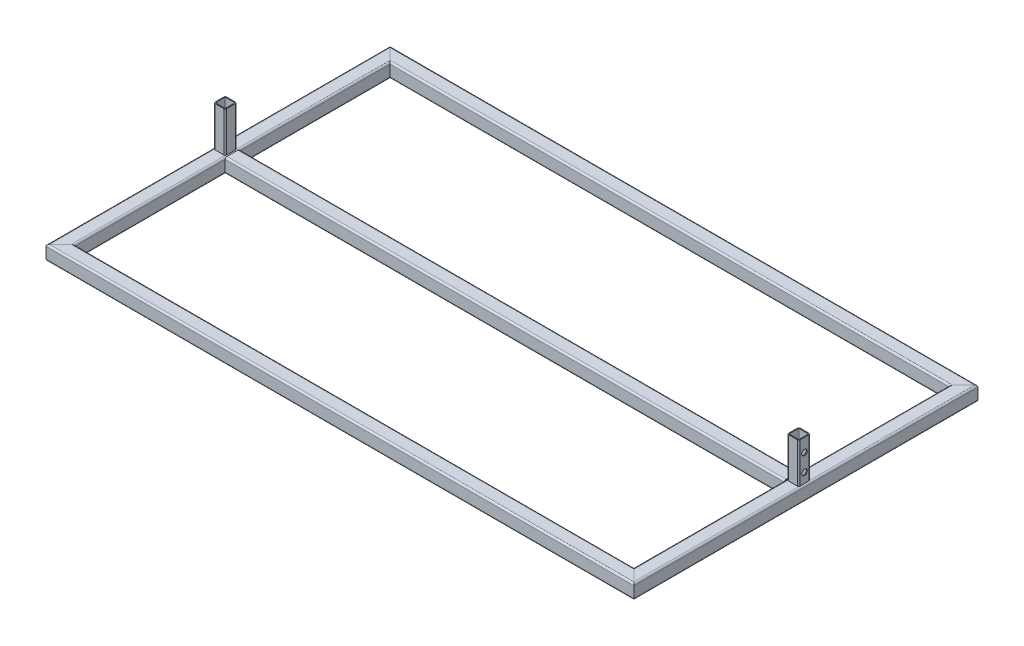
SolidWorks part; units mm, degrees
ref_plane "Спереди" through (0, 0, 0) normal (0, 0, 1) x (1, 0, 0)
ref_plane "Сверху" through (0, 0, 0) normal (0, 1, 0) x (1, 0, 0)
ref_plane "Справа" through (0, 0, 0) normal (1, 0, 0) x (0, 0, -1)
sketch "Эскиз1" plane through (0, 0, 0) normal (0, 1, 0) x (1, 0, 0)
  line L1 (-500, -287.5) -> (500, -287.5)
  line L2 (-500, -287.5) -> (-500, 287.5)
  line L3 (-500, 287.5) -> (500, 287.5)
  line L4 (500, -287.5) -> (500, 287.5)
  line L5 (0, 287.5) -> (0, -287.5) construction
  line L6 (-500, 0) -> (500, 0)
  point P0 (0, 0)
  dimension "D1" = 575
  dimension "D2" = 1000
sketch3d "Трехмерный эскиз1"
  line L0 (-500, 0, 0) -> (-500, 82.5, 0)
  line L1 (500, 0, 0) -> (500, 82.5, 0)
  dimension "D1" = 82.5
other "Square tube - configured 20 X 20 X 2(1)"
ref_plane "Плоскость1" through (-500, 0, -287.5) normal (1, 0, 0) x (0, 0, -1)
sketch "Sketch11" plane through (-500, 0, -287.5) normal (1, 0, 0) x (0, 0, -1)
  line L0 (-9.5, -11) -> (9.5, -11)
  line L1 (-11, -9.5) -> (-11, 9.5)
  line L2 (9.5, 11) -> (-9.5, 11)
  line L3 (11, 9.5) -> (11, -9.5)
  line L4 (-9.5, -12.5) -> (9.5, -12.5)
  line L5 (-12.5, -9.5) -> (-12.5, 9.5)
  line L6 (9.5, 12.5) -> (-9.5, 12.5)
  line L7 (12.5, 9.5) -> (12.5, -9.5)
  arc A0 (12.5, 9.5) -> (9.5, 12.5) centre (9.5, 9.5) ccw
  arc A1 (9.5, -12.5) -> (12.5, -9.5) centre (9.5, -9.5) ccw
  arc A2 (-12.5, -9.5) -> (-9.5, -12.5) centre (-9.5, -9.5) ccw
  arc A3 (-9.5, 12.5) -> (-12.5, 9.5) centre (-9.5, 9.5) ccw
  arc A4 (-9.5, 11) -> (-11, 9.5) centre (-9.5, 9.5) ccw
  arc A5 (11, 9.5) -> (9.5, 11) centre (9.5, 9.5) ccw
  arc A6 (9.5, -11) -> (11, -9.5) centre (9.5, -9.5) ccw
  arc A7 (-11, -9.5) -> (-9.5, -11) centre (-9.5, -9.5) ccw
  point P0 (-12.5, 0)
  point P1 (12.5, 0)
  point P2 (0, 12.5)
  point P3 (0, -12.5)
  point P4 (0, 0)
  point P5 (-12.5, -12.5)
  point P6 (12.5, -12.5)
  point P7 (12.5, 12.5)
  point P8 (-12.5, 12.5)
  point P33 (0, 0)
  dimension "D1" = 3
  dimension "Thickness" = 1.5
  dimension "V_leg" = 25
other "Square tube - configured 20 X 20 X 2(2)"
ref_plane "Плоскость2" through (-500, 0, 0) normal (0, 1, 0) x (1, 0, 0)
sketch "Sketch1" plane through (-500, 0, 0) normal (0, 1, 0) x (1, 0, 0)
  line L0 (-7.5, -8.5) -> (7.5, -8.5)
  line L1 (-8.5, -7.5) -> (-8.5, 7.5)
  line L2 (7.5, 8.5) -> (-7.5, 8.5)
  line L3 (8.5, 7.5) -> (8.5, -7.5)
  line L4 (-7.5, -10) -> (7.5, -10)
  line L5 (-10, -7.5) -> (-10, 7.5)
  line L6 (7.5, 10) -> (-7.5, 10)
  line L7 (10, 7.5) -> (10, -7.5)
  arc A0 (10, 7.5) -> (7.5, 10) centre (7.5, 7.5) ccw
  arc A1 (7.5, -10) -> (10, -7.5) centre (7.5, -7.5) ccw
  arc A2 (-10, -7.5) -> (-7.5, -10) centre (-7.5, -7.5) ccw
  arc A3 (-7.5, 10) -> (-10, 7.5) centre (-7.5, 7.5) ccw
  arc A4 (-7.5, 8.5) -> (-8.5, 7.5) centre (-7.5, 7.5) ccw
  arc A5 (8.5, 7.5) -> (7.5, 8.5) centre (7.5, 7.5) ccw
  arc A6 (7.5, -8.5) -> (8.5, -7.5) centre (7.5, -7.5) ccw
  arc A7 (-8.5, -7.5) -> (-7.5, -8.5) centre (-7.5, -7.5) ccw
  point P0 (-10, 0)
  point P1 (10, 0)
  point P2 (0, 10)
  point P3 (0, -10)
  point P4 (0, 0)
  point P5 (-10, -10)
  point P6 (10, -10)
  point P7 (10, 10)
  point P8 (-10, 10)
  point P33 (0, 0)
  dimension "D1" = 2.5
  dimension "Thickness" = 1.5
  dimension "V_leg" = 20
other "Отсечь/Удлинить1"
sketch "Эскиз3" plane through (0, -12.5, 0) normal (0, -1, 0) x (-1, 0, 0)
  line L1 (500, -287.5) -> (461.8661, -287.5) construction
  line L2 (509.5, -297) -> (490.5, -278) construction
  line L4 (482.1132, -292.5) -> (487.8868, -292.5)
  line L5 (487.8868, -292.5) -> (490.7735, -287.5)
  line L6 (490.7735, -287.5) -> (487.8868, -282.5)
  line L7 (487.8868, -282.5) -> (482.1132, -282.5)
  line L8 (482.1132, -282.5) -> (479.2265, -287.5)
  line L9 (479.2265, -287.5) -> (482.1132, -292.5)
  circle A1 centre (485, -287.5) radius 5 construction
  dimension "D1" = 10
  dimension "D2" = 15
extrude "Вырез-Вытянуть2" cut sketch "Эскиз3" against normal blind 5
mirror "Зеркальное отражение1" about plane through (0, 0, 0) normal (1, 0, 0) of "Вырез-Вытянуть2"
mirror "Зеркальное отражение2" about plane through (0, 0, 0) normal (0, 0, 1) of "Зеркальное отражение1", "Вырез-Вытянуть2"
ref_plane "Плоскость3" through (-500, 0, 0) normal (1, 0, 0) x (0, 0, -1)
sketch "Эскиз4" plane through (-510, 0, 0) normal (1, 0, 0) x (0, 0, -1)
  line L1 (-5.3116, 59.5) -> (-2.6558, 54.9)
  line L2 (-2.6558, 54.9) -> (2.6558, 54.9)
  line L3 (2.6558, 54.9) -> (5.3116, 59.5)
  line L4 (5.3116, 59.5) -> (2.6558, 64.1)
  line L5 (2.6558, 64.1) -> (-2.6558, 64.1)
  line L6 (-2.6558, 64.1) -> (-5.3116, 59.5)
  line L7 (-5.3116, 29.5) -> (-2.6558, 24.9)
  line L8 (-2.6558, 24.9) -> (2.6558, 24.9)
  line L9 (2.6558, 24.9) -> (5.3116, 29.5)
  line L10 (5.3116, 29.5) -> (2.6558, 34.1)
  line L11 (2.6558, 34.1) -> (-2.6558, 34.1)
  line L12 (-2.6558, 34.1) -> (-5.3116, 29.5)
  circle A0 centre (0, 59.5) radius 4.6 construction
  circle A1 centre (0, 29.5) radius 3.75
  circle A2 centre (0, 29.5) radius 3.75 construction
  circle A3 centre (0, 59.5) radius 3.75
  circle A4 centre (0, 59.5) radius 3.75 construction
  circle A5 centre (0, 29.5) radius 4.6 construction
  dimension "D3" = 9.2
  dimension "D4" = 9.2
  dimension "D1" = 0
  dimension "D2" = 0
extrude "Вырез-Вытянуть3" cut sketch "Эскиз4" along normal up to next (1.5 mm away) from surface at 0 starting at face at (-510, 47.5, 0)
sketch "Эскиз5" plane through (510, 0, 0) normal (1, 0, 0) x (0, 0, -1)
  line L6 (-5.3116, 59.5) -> (-2.6558, 54.9)
  line L7 (-2.6558, 54.9) -> (2.6558, 54.9)
  line L8 (2.6558, 54.9) -> (5.3116, 59.5)
  line L9 (5.3116, 59.5) -> (2.6558, 64.1)
  line L10 (2.6558, 64.1) -> (-2.6558, 64.1)
  line L11 (-2.6558, 64.1) -> (-5.3116, 59.5)
  line L12 (-5.3116, 59.5) -> (-2.6558, 54.9)
  line L13 (-2.6558, 54.9) -> (2.6558, 54.9)
  line L14 (2.6558, 54.9) -> (5.3116, 59.5)
  line L15 (5.3116, 59.5) -> (2.6558, 64.1)
  line L16 (2.6558, 64.1) -> (-2.6558, 64.1)
  line L17 (-2.6558, 64.1) -> (-5.3116, 59.5)
  line L18 (2.6558, 24.9) -> (5.3116, 29.5)
  line L19 (5.3116, 29.5) -> (2.6558, 34.1)
  line L20 (2.6558, 34.1) -> (-2.6558, 34.1)
  line L21 (-2.6558, 34.1) -> (-5.3116, 29.5)
  line L22 (-5.3116, 29.5) -> (-2.6558, 24.9)
  line L23 (-2.6558, 24.9) -> (2.6558, 24.9)
  line L24 (2.6558, 24.9) -> (5.3116, 29.5)
  line L25 (5.3116, 29.5) -> (2.6558, 34.1)
  line L26 (2.6558, 34.1) -> (-2.6558, 34.1)
  line L27 (-2.6558, 34.1) -> (-5.3116, 29.5)
  line L28 (-5.3116, 29.5) -> (-2.6558, 24.9)
  line L29 (-2.6558, 24.9) -> (2.6558, 24.9)
  dimension "D1" = 0
  dimension "D2" = 0
extrude "Вырез-Вытянуть4" cut sketch "Эскиз5" against normal up to next (1.5 mm away)
equation "\"шестигранная зинковка\"=9.2"
equation "\"D3@Эскиз4\"=\"шестигранная зинковка\""
equation "\"D4@Эскиз4\"=\"шестигранная зинковка\""
